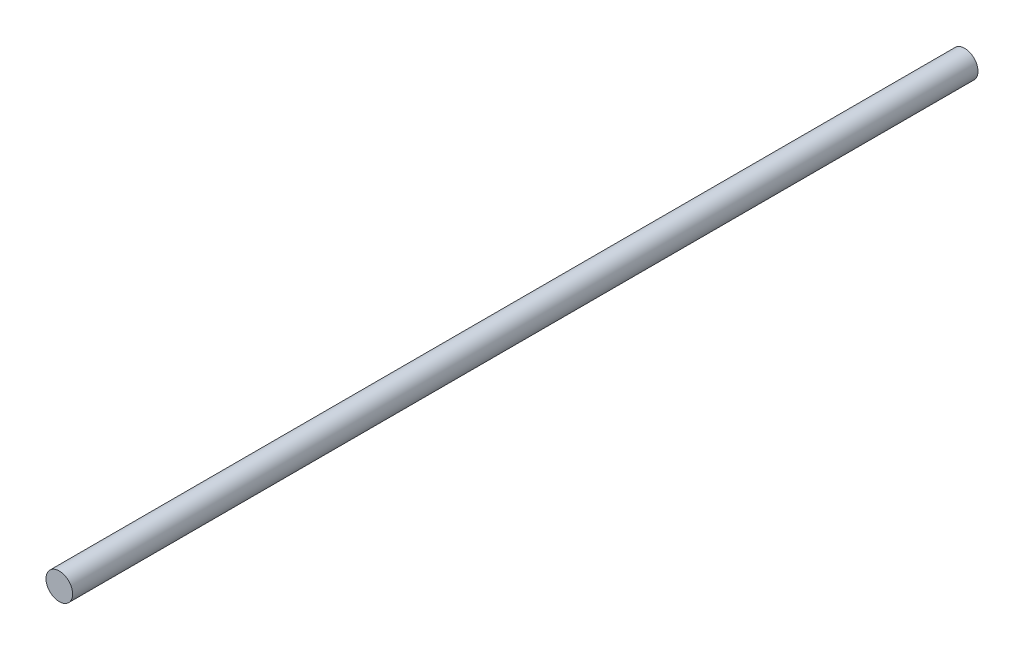
SolidWorks part; units mm, degrees
ref_plane "정면" through (0, 0, 0) normal (0, 0, 1) x (1, 0, 0)
ref_plane "윗면" through (0, 0, 0) normal (0, 1, 0) x (1, 0, 0)
ref_plane "우측면" through (0, 0, 0) normal (1, 0, 0) x (0, 0, -1)
sketch "스케치1" plane through (0, 0, 0) normal (0, 0, 1) x (1, 0, 0)
  circle A0 centre (0, 0) radius 3
  dimension "D1" = 6
extrude "보스-돌출1" add sketch "스케치1" along normal blind 204
